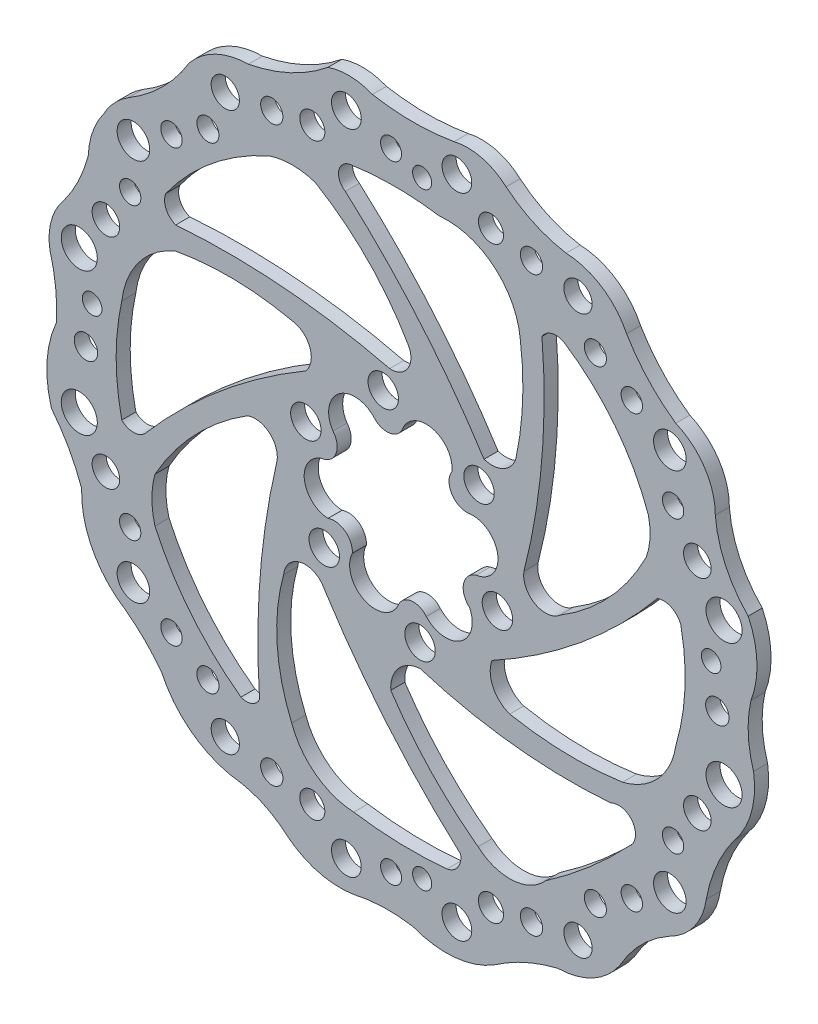
SolidWorks part; units mm, degrees
material "Alumina"
ref_plane "Front Plane" through (0, 0, 0) normal (0, 0, 1) x (1, 0, 0)
ref_plane "Top Plane" through (0, 0, 0) normal (0, 1, 0) x (1, 0, 0)
ref_plane "Right Plane" through (0, 0, 0) normal (1, 0, 0) x (0, 0, -1)
sketch "Sketch1" plane through (0, 0, 0) normal (0, 0, 1) x (1, 0, 0)
  line L0 (61.9731, 183.9202) -> (309.8656, 183.9202) construction
  line L1 (184.8369, 177.6432) -> (184.8369, 194.4656) construction
  line L2 (184.8369, 177.6432) -> (204.1866, 177.6432) construction
  circle A0 centre (143.9457, 192.1808) radius 6.5
  circle A1 centre (184.8369, 177.6432) radius 153.5 construction
  circle A3 centre (184.8369, 177.6432) radius 43.3986 construction
  circle A4 centre (176.9813, 220.3249) radius 6.5
  circle A5 centre (217.8725, 205.7873) radius 6.5
  circle A6 centre (225.7282, 163.1056) radius 6.5
  circle A7 centre (192.6926, 134.9616) radius 6.5
  circle A8 centre (151.8014, 149.4992) radius 6.5
  arc A9 (84.1075, 246.5907) -> (128.298, 282.6115) centre (172.3503, 183.4509) cw
  arc A10 (147.9795, 282.6115) -> (187.6806, 242.378) centre (91.4144, 187.0903) cw
  arc A11 (88.378, 237.1213) -> (179.7298, 229.6943) centre (110.6834, -54.0497) cw
  arc A12 (162.8334, 296.7228) -> (200.8967, 296.7228) centre (181.8651, 170.3713) cw
  arc A13 (235.4322, 268.8716) -> (233.5754, 223.1957) centre (104.6995, 251.3102) cw
  arc A14 (160.791, 285.768) -> (220.0212, 216.3257) centre (-60.5971, 36.9559) cw
  arc A15 (128.298, 282.6115) -> (147.9795, 282.6115) centre (138.1387, 253.0312) cw
  arc A16 (84.1075, 246.5907) -> (88.378, 237.1213) centre (90.9774, 243.9912) ccw
  arc A17 (179.7298, 229.6943) -> (187.6806, 242.378) centre (180.3263, 238.1542) ccw
  arc A18 (162.8334, 296.7228) -> (160.791, 285.768) centre (163.8135, 290.8723) ccw
  arc A19 (200.8967, 296.7228) -> (235.4322, 268.8716) centre (204.2388, 265.5295) cw
  arc A20 (220.0212, 216.3257) -> (233.5754, 223.1957) centre (223.3633, 226.5378) ccw
  arc A21 (244.7348, 274.0865) -> (237.0543, 183.4509) centre (-27.9728, 251.5525) cw
  arc A22 (254.2977, 276.5446) -> (290.1223, 230.9091) centre (204.1866, 200.3274) cw
  arc A23 (289.2304, 214.7063) -> (252.3653, 174.8682) centre (202.0574, 258.3977) cw
  arc A24 (237.0543, 183.4509) -> (252.3653, 174.8682) centre (246.2572, 181.9201) ccw
  arc A25 (289.2304, 214.7063) -> (290.1223, 230.9091) centre (262.8893, 224.2822) ccw
  arc A26 (254.2977, 276.5446) -> (244.7348, 274.0865) centre (250.7453, 270.5341) ccw
  arc A27 (138.1387, 226.5378) -> (88.378, 227.4375) centre (111.0371, 104.1342) ccw
  arc A28 (65.3772, 197.5379) -> (65.3772, 153.4871) centre (164.3636, 175.5125) ccw
  arc A29 (75.2878, 153.4871) -> (143.9457, 210.963) centre (280.8617, -22.3356) cw
  arc A30 (138.1387, 226.5378) -> (143.9457, 210.963) centre (136.7988, 217.1683) cw
  arc A31 (88.378, 227.4375) -> (65.3772, 197.5379) centre (102.1358, 193.0574) ccw
  arc A32 (75.2878, 153.4871) -> (65.3772, 153.4871) centre (70.3325, 158.4424) cw
  arc A33 (119.0244, 181.9201) -> (79.5299, 140.555) centre (180.1946, 83.9793) ccw
  arc A34 (79.5299, 121.3614) -> (116.2561, 76.5149) centre (182.5195, 168.2414) ccw
  arc A35 (131.3895, 170.3713) -> (124.1919, 79.6523) centre (430.0262, 101.0326) ccw
  arc A36 (124.1919, 79.6523) -> (116.2561, 76.5149) centre (118.6553, 82.0515) cw
  arc A37 (79.5299, 140.555) -> (79.5299, 121.3614) centre (113.6855, 130.9582) ccw
  arc A38 (119.0244, 181.9201) -> (131.3895, 170.3713) centre (122.2649, 172.9957) cw
  arc A39 (134.4823, 130.9582) -> (137.9052, 77.7312) centre (212.0219, 109.2209) ccw
  arc A40 (151.8014, 134.2447) -> (210.0225, 65.3007) centre (433.4213, 313.0092) ccw
  arc A41 (204.1866, 56.9391) -> (164.3636, 58.0384) centre (188.7837, 220.8185) cw
  arc A42 (164.3636, 58.0384) -> (137.9052, 77.7312) centre (165.8969, 87.7191) cw
  arc A43 (210.0225, 65.3007) -> (204.1866, 56.9391) centre (202.9237, 64.0379) cw
  arc A44 (151.8014, 134.2447) -> (134.4823, 130.9582) centre (143.6238, 130.0616) ccw
  arc A45 (192.6926, 125.2804) -> (274.2028, 116.3192) centre (256.9038, 334.1545) ccw
  arc A46 (180.1946, 110.9876) -> (217.4521, 71.8156) centre (309.8585, 197.01) ccw
  arc A47 (246.2572, 73.6008) -> (281.9996, 104.366) centre (118.6523, 257.9948) ccw
  arc A48 (217.4521, 71.8156) -> (246.2572, 73.6008) centre (230.962, 87.1108) ccw
  arc A49 (281.9996, 104.366) -> (274.2028, 116.3192) centre (277.5014, 109.9513) ccw
  arc A50 (192.6926, 125.2804) -> (180.1946, 110.9876) centre (193.59, 111.8849) ccw
  arc A51 (294.0775, 201.8861) -> (223.3633, 143.6136) centre (106.944, 356.9319) cw
  arc A52 (304.0423, 197.01) -> (301.876, 151.4121) centre (211.9371, 178.5353) cw
  arc A53 (230.962, 127.5833) -> (279.1199, 126.4808) centre (258.3075, 269.7276) ccw
  arc A54 (279.1199, 126.4808) -> (301.876, 151.4121) centre (272.0777, 155.7596) ccw
  arc A55 (223.3633, 143.6136) -> (230.962, 127.5833) centre (235.1778, 139.3978) ccw
  arc A56 (294.0775, 201.8861) -> (304.0423, 197.01) centre (296.6218, 194.4656) cw
  circle A57 centre (180.3263, 311.4171) radius 4.4819
  circle A58 centre (161.2517, 315.8991) radius 6.3519
  circle A59 centre (146.6977, 303.2011) radius 5.363
  circle A60 centre (129.4023, 299.9167) radius 4.7526
  circle A61 centre (109.5577, 296.7228) radius 6.0347
  circle A62 centre (102.1358, 279.4436) radius 4.7117
  circle A63 centre (86.5753, 269.7276) radius 4.5688
  circle A64 centre (70.3325, 259.4025) radius 6.9551
  circle A65 centre (68.9535, 239.5634) radius 4.5461
  circle A66 centre (58.6013, 224.2822) radius 5.8887
  circle A67 centre (47.213, 208.0251) radius 7.6977
  circle A68 centre (52.7125, 190.1778) radius 4.1878
  circle A69 centre (50.0679, 172.9957) radius 4.9974
  circle A71 centre (208.4221, 315.8991) radius 6.3519
  circle A72 centre (222.9762, 303.2011) radius 5.363
  circle A73 centre (240.2715, 299.9167) radius 4.7526
  circle A74 centre (260.1162, 296.7228) radius 6.0347
  circle A75 centre (267.538, 279.4436) radius 4.7117
  circle A76 centre (283.0986, 269.7276) radius 4.5688
  circle A77 centre (299.3414, 259.4025) radius 6.9551
  circle A78 centre (300.7204, 239.5634) radius 4.5461
  circle A79 centre (311.0726, 224.2822) radius 5.8887
  circle A80 centre (322.4609, 208.0251) radius 7.6977
  circle A81 centre (316.9614, 190.1778) radius 4.1878
  circle A82 centre (319.6059, 172.9957) radius 4.9974
  circle A83 centre (193.59, 307.2478) radius 4.0856
  circle A86 centre (322.4609, 147.2613) radius 7.6977
  circle A87 centre (311.0726, 131.0042) radius 5.8887
  circle A88 centre (300.7204, 115.7231) radius 4.5461
  circle A89 centre (299.3414, 95.8839) radius 6.9551
  circle A90 centre (283.0986, 85.5588) radius 4.5688
  circle A91 centre (267.538, 75.8429) radius 4.7117
  circle A92 centre (260.1162, 58.5637) radius 6.0347
  circle A93 centre (240.2715, 55.3697) radius 4.7526
  circle A94 centre (222.9762, 52.0853) radius 5.363
  circle A95 centre (208.4221, 39.3874) radius 6.3519
  circle A96 centre (193.59, 48.0386) radius 4.0856
  circle A97 centre (180.3263, 43.8693) radius 4.4819
  circle A98 centre (161.2517, 39.3874) radius 6.3519
  circle A99 centre (146.6977, 52.0853) radius 5.363
  circle A100 centre (129.4023, 55.3697) radius 4.7526
  circle A101 centre (109.5577, 58.5637) radius 6.0347
  circle A102 centre (102.1358, 75.8429) radius 4.7117
  circle A103 centre (86.5753, 85.5588) radius 4.5688
  circle A104 centre (70.3325, 95.8839) radius 6.9551
  circle A105 centre (68.9535, 115.7231) radius 4.5461
  circle A106 centre (58.6013, 131.0042) radius 5.8887
  circle A107 centre (47.213, 147.2613) radius 7.6977
  arc A108 (172.3503, 327.344) -> (207.235, 327.344) centre (189.7926, 426.4836) ccw
  arc A109 (207.235, 327.344) -> (229.4098, 321.7382) centre (212.9994, 303.4848) cw
  arc A110 (229.4098, 321.7382) -> (255.0611, 310.0348) centre (263.8991, 363.3682) ccw
  arc A111 (255.0611, 310.0348) -> (280.8617, 293.142) centre (253.8411, 280.0222) cw
  arc A112 (280.8617, 293.142) -> (301.876, 270.5341) centre (343.2347, 330.0481) ccw
  arc A113 (301.876, 270.5341) -> (318.7384, 245.0141) centre (291.1232, 245.0983) cw
  arc A114 (318.7384, 245.0141) -> (332.7815, 214.7063) centre (367.1786, 249.0515) ccw
  arc A115 (332.7815, 214.7063) -> (333.9482, 184.1283) centre (297.8383, 198.0618) cw
  arc A116 (333.9482, 184.1283) -> (335.075, 158.4424) centre (381.6272, 173.3522) ccw
  arc A117 (335.075, 158.4424) -> (326.8065, 128.837) centre (298.1772, 152.7903) cw
  arc A118 (326.8065, 128.837) -> (314.8742, 101.0326) centre (381.3399, 88.9715) ccw
  arc A119 (314.8742, 101.0326) -> (299.3414, 79.6523) centre (286.7657, 105.1211) cw
  arc A120 (299.3414, 79.6523) -> (278.22, 58.5637) centre (325.4982, 32.3335) ccw
  arc A121 (278.22, 58.5637) -> (251.5077, 43.8693) centre (251.0721, 76.288) cw
  arc A122 (251.5077, 43.8693) -> (224.2321, 31.4646) centre (270.6358, -34.3792) ccw
  arc A123 (224.2321, 31.4646) -> (189.7926, 28.3558) centre (203.8611, 64.8191) cw
  arc A124 (189.7926, 28.3558) -> (164.3636, 27.6104) centre (178.9686, -36.5153) ccw
  arc A125 (164.3636, 27.6104) -> (135.7423, 35.2659) centre (158.5053, 63.0387) cw
  arc A126 (135.7423, 35.2659) -> (116.2561, 44.7681) centre (108.8868, 4.9244) ccw
  arc A127 (116.2561, 44.7681) -> (82.4413, 68.5987) centre (120.3859, 86.5343) cw
  arc A128 (82.4413, 68.5987) -> (67.072, 83.9793) centre (23.3501, 24.9205) ccw
  arc A129 (67.072, 83.9793) -> (48.236, 119.5907) centre (88.7985, 118.2584) cw
  arc A130 (48.236, 119.5907) -> (35.3557, 142.7491) centre (-25.3048, 93.8495) ccw
  arc A131 (35.3557, 142.7491) -> (37.4357, 175.5125) centre (80.3931, 156.3376) cw
  arc A132 (37.4357, 175.5125) -> (34.683, 201.0256) centre (-38.083, 180.2697) ccw
  arc A133 (34.683, 201.0256) -> (40.4682, 222.0867) centre (60.3765, 205.2931) cw
  arc A134 (40.4682, 222.0867) -> (51.042, 243.9912) centre (-10.3063, 260.101) ccw
  arc A135 (51.042, 243.9912) -> (57.5763, 262.719) centre (85.0206, 242.6396) cw
  arc A136 (57.5763, 262.719) -> (68.1991, 274.0865) centre (84.0982, 248.582) cw
  arc A137 (68.1991, 274.0865) -> (94.1464, 299.9167) centre (30.1587, 338.2469) ccw
  arc A138 (94.1464, 299.9167) -> (119.3904, 312.0606) centre (119.7309, 279.043) cw
  arc A139 (119.3904, 312.0606) -> (153.3694, 327.8832) centre (104.9455, 387.4774) ccw
  arc A140 (153.3694, 327.8832) -> (172.3503, 327.344) centre (162.1475, 302.5385) cw
  arc A142 (173.3149, 208.0251) -> (155.5315, 194.4656) centre (164.8748, 200.6531) ccw
  arc A143 (173.3149, 208.0251) -> (185.5474, 210.963) centre (178.5984, 212.9613) ccw
  arc A144 (185.5474, 210.963) -> (206.3414, 204.9833) centre (195.361, 205.9446) cw
  arc A145 (206.3414, 204.9833) -> (213.8158, 193.0574) centre (212.7827, 200.7151) ccw
  arc A146 (213.8158, 193.0574) -> (216.6837, 171.7992) centre (215.2497, 182.4283) cw
  arc A147 (216.6837, 171.7992) -> (213.8158, 158.4424) centre (218.8829, 164.3407) ccw
  arc A148 (213.8158, 158.4424) -> (195.361, 145.8333) centre (203.6768, 153.4722) cw
  arc A149 (195.361, 145.8333) -> (183.2042, 143.6136) centre (189.8774, 141.4662) ccw
  arc A150 (183.2042, 143.6136) -> (163.8135, 153.4722) centre (173.5088, 148.5429) cw
  arc A151 (163.8135, 153.4722) -> (153.3694, 161.1391) centre (156.0794, 153.8837) ccw
  arc A152 (153.3694, 161.1391) -> (150.4827, 181.9201) centre (153.9076, 171.8049) cw
  arc A153 (150.4827, 181.9201) -> (155.5315, 194.4656) centre (149.634, 189.5503) ccw
  dimension "D1" = 307
  dimension "D4" = 13
  dimension "D2" = 177.6432
  dimension "D3" = 184.8369
extrude "Boss-Extrude2" add sketch "Sketch1" along normal mid plane 6
